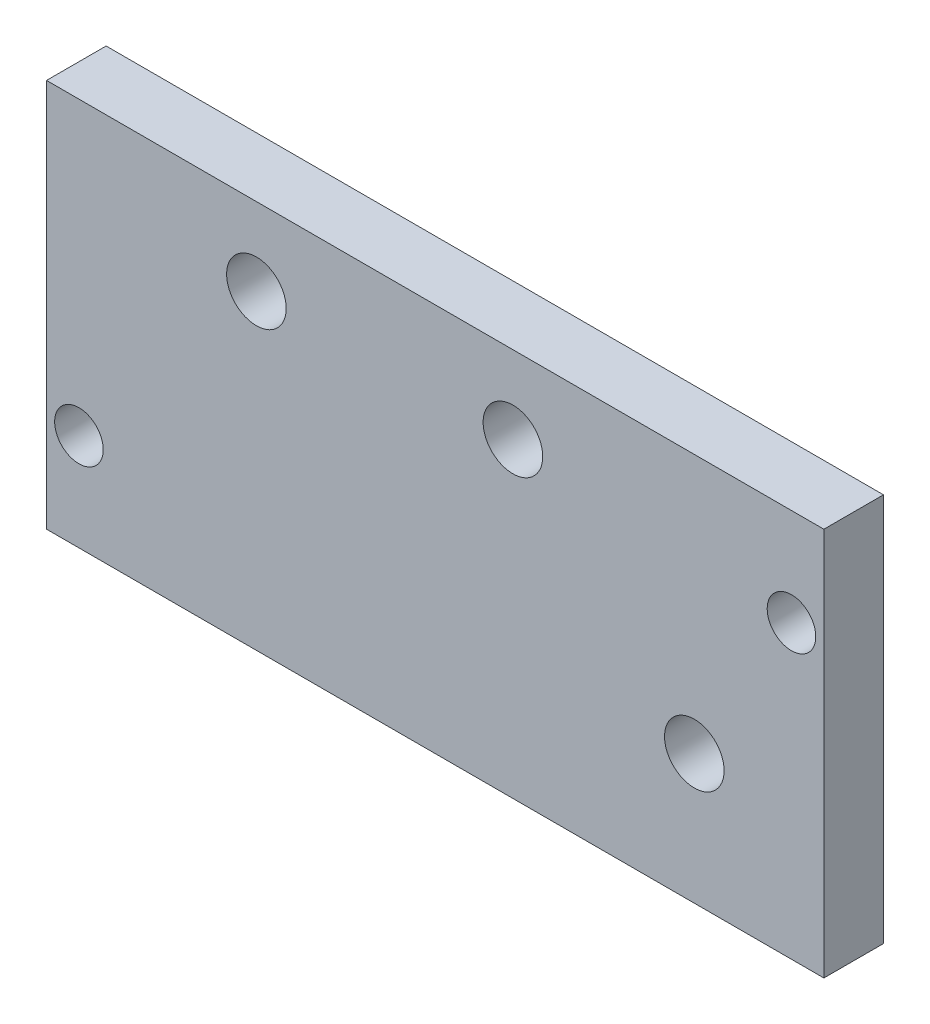
SolidWorks part; units mm, degrees
ref_plane "Front Plane" through (0, 0, 0) normal (0, 0, 1) x (1, 0, 0)
ref_plane "Top Plane" through (0, 0, 0) normal (0, 1, 0) x (1, 0, 0)
ref_plane "Right Plane" through (0, 0, 0) normal (1, 0, 0) x (0, 0, -1)
sketch "Sketch1" plane through (0, 0, 0) normal (0, 0, 1) x (1, 0, 0)
  line L0 (5.9993, 9.0007) -> (20, -5) construction
  line L1 (-30, -15) -> (30, -15)
  line L2 (-30, -15) -> (-30, 15)
  line L3 (-30, 15) -> (30, 15)
  line L4 (30, -15) -> (30, 15)
  line L5 (-30, -15) -> (30, 15) construction
  line L6 (-30, 15) -> (30, -15) construction
  circle A0 centre (-13.8007, 9.0007) radius 2.3
  circle A1 centre (5.9993, 9.0007) radius 2.3
  circle A2 centre (20, -5) radius 2.3
  point P0 (0, 0)
  dimension "D1" = 4.6
  dimension "D7" = 10
  dimension "D3" = 19.8
  dimension "D5" = 19.8
  dimension "D6" = 10
  dimension "D8" = 30
  dimension "D9" = 60
  dimension "D10" = 45
extrude "Boss-Extrude1" add sketch "Sketch1" along normal blind 4.6
sketch "Sketch2" plane through (0, 0, 4.6) normal (0, 0, 1) x (1, 0, 0)
  line L0 (-30, -15) -> (30, -15) construction
  line L1 (-30, 15) -> (-30, -15) construction
  line L2 (30, 15) -> (-30, 15) construction
  line L3 (30, -15) -> (30, 15) construction
  circle A0 centre (-27.5, -7.5) radius 1.875
  circle A1 centre (27.5, 7.5) radius 1.875
  dimension "D2" = 2.5
  dimension "D3" = 3.75
  dimension "D4" = 7.5
  dimension "D5" = 2.5
  dimension "D1" = 7.5
extrude "Cut-Extrude1" cut sketch "Sketch2" against normal up to next and the other way through all
equation "\"shaftHole\"=4.05"
